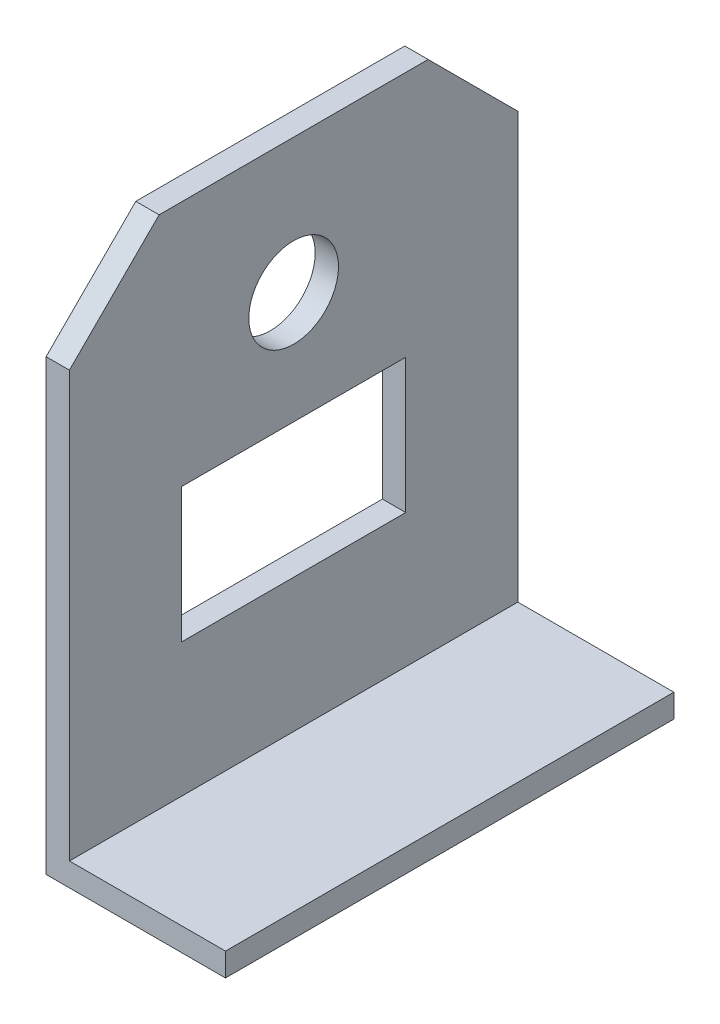
SolidWorks part; units mm, degrees
material "6061-T6 (SS)"
ref_plane "Front Plane" through (0, 0, 0) normal (0, 0, 1) x (1, 0, 0)
ref_plane "Top Plane" through (0, 0, 0) normal (0, 1, 0) x (1, 0, 0)
ref_plane "Right Plane" through (0, 0, 0) normal (1, 0, 0) x (0, 0, -1)
sketch "Sketch4" plane through (0, 0, 0) normal (0, 0, 1) x (1, 0, 0)
  line L0 (0, 0) -> (0, 76.2)
  line L1 (0, 76.2) -> (3.302, 76.2)
  line L2 (3.302, 76.2) -> (3.302, 3.302)
  line L3 (3.302, 3.302) -> (25.4, 3.302)
  line L4 (25.4, 3.302) -> (25.4, 0)
  line L5 (25.4, 0) -> (0, 0)
  dimension "D1" = 76.2
  dimension "D2" = 3.302
  dimension "D3" = 3.302
  dimension "D4" = 25.4
extrude "Boss-Extrude1" add sketch "Sketch4" along normal mid plane 63.5
sketch "Sketch5" plane through (3.302, 0, 0) normal (1, 0, 0) x (0, 0, -1)
  line L0 (-31.75, 3.302) -> (-31.75, 76.2) construction
  line L1 (-31.75, 76.2) -> (31.75, 76.2) construction
  line L2 (-31.75, 63.5) -> (-31.75, 76.2)
  line L3 (15.875, 41.275) -> (-15.875, 41.275)
  line L4 (15.875, 41.275) -> (15.875, 22.225)
  line L5 (15.875, 22.225) -> (-15.875, 22.225)
  line L6 (-15.875, 41.275) -> (-15.875, 22.225)
  line L7 (15.875, 41.275) -> (-15.875, 22.225) construction
  line L8 (15.875, 22.225) -> (-15.875, 41.275) construction
  line L9 (-31.75, 76.2) -> (-19.05, 76.2)
  line L10 (-19.05, 76.2) -> (-31.75, 63.5)
  line L11 (19.05, 76.2) -> (31.75, 63.5)
  line L12 (31.75, 3.302) -> (31.75, 76.2) construction
  line L13 (31.75, 63.5) -> (31.75, 76.2)
  line L14 (31.75, 76.2) -> (19.05, 76.2)
  circle A0 centre (0, 57.15) radius 6.35
  point P6 (0, 31.75)
  point P19 (0, 0)
  point P22 (0, 0)
  point P23 (0, 0)
  point P25 (0, 0)
  dimension "D3" = 12.7
  dimension "D2" = 19.05
  dimension "D4" = 31.75
  dimension "D5" = 19.05
  dimension "D6" = 25.4
  dimension "D7" = 12.7
  dimension "D8" = 12.7
  dimension "D9" = 12.7
  dimension "D10" = 12.7
extrude "Cut-Extrude1" cut sketch "Sketch5" against normal up to surface (3.302 mm away) up to face at (0, 38.1, 0)
